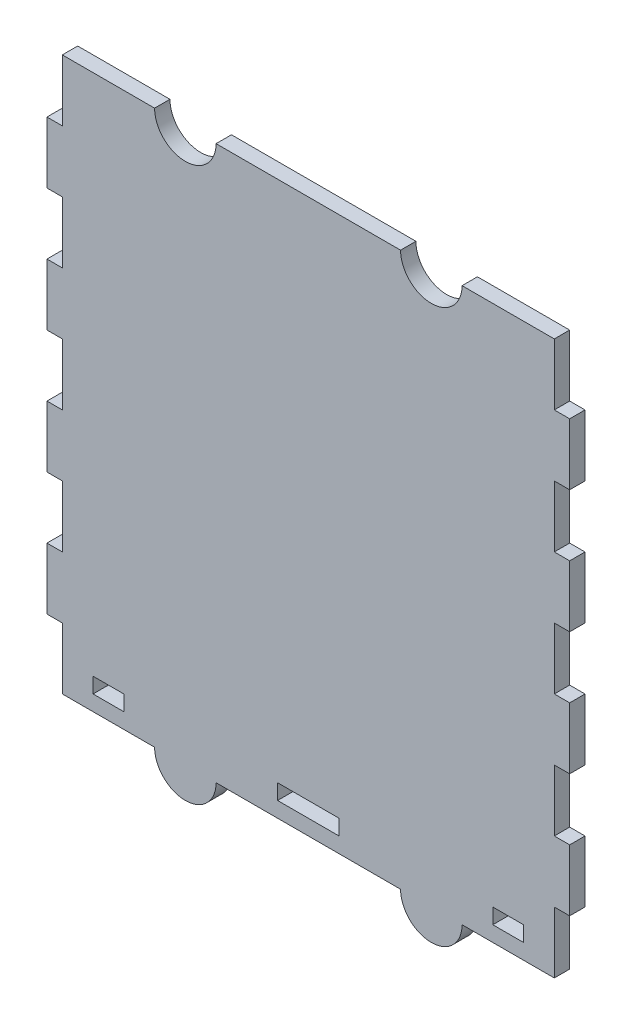
SolidWorks part; units mm, degrees
ref_plane "Front Plane" through (0, 0, 0) normal (0, 0, 1) x (1, 0, 0)
ref_plane "Top Plane" through (0, 0, 0) normal (0, 1, 0) x (1, 0, 0)
ref_plane "Right Plane" through (0, 0, 0) normal (1, 0, 0) x (0, 0, -1)
sketch "Sketch1" plane through (0, 0, 0) normal (0, 0, 1) x (1, 0, 0)
  line L0 (42.5, 60) -> (42.5, 50)
  line L1 (-15, 0) -> (15, 0)
  line L2 (25, 90) -> (40, 90)
  line L3 (-15, 90) -> (15, 90)
  line L4 (40, 0) -> (40, 10)
  line L5 (40, 80) -> (42.5, 80)
  line L6 (40, 80) -> (40, 90)
  line L7 (40, 70) -> (42.5, 70)
  line L8 (42.5, 80) -> (42.5, 70)
  line L9 (40, 50) -> (42.5, 50)
  line L10 (40, 60) -> (42.5, 60)
  line L11 (42.5, 40) -> (42.5, 30)
  line L12 (40, 30) -> (42.5, 30)
  line L13 (40, 40) -> (42.5, 40)
  line L14 (42.5, 20) -> (42.5, 10)
  line L15 (40, 10) -> (42.5, 10)
  line L16 (40, 20) -> (42.5, 20)
  line L17 (40, 20) -> (40, 30)
  line L18 (40, 40) -> (40, 50)
  line L19 (40, 60) -> (40, 70)
  line L20 (0, 90) -> (0, 0) construction
  line L21 (25, 0) -> (40, 0)
  line L22 (-5, 5) -> (-5, 2.5)
  line L23 (35, 5) -> (30, 5)
  line L24 (35, 5) -> (35, 2.5)
  line L25 (35, 2.5) -> (30, 2.5)
  line L26 (30, 5) -> (30, 2.5)
  line L27 (5, 5) -> (-5, 5)
  line L28 (5, 5) -> (5, 2.5)
  line L29 (5, 2.5) -> (-5, 2.5)
  line L30 (-30, 5) -> (-30, 2.5)
  line L31 (-35, 2.5) -> (-30, 2.5)
  line L32 (-35, 5) -> (-35, 2.5)
  line L33 (-35, 5) -> (-30, 5)
  line L34 (-25, 0) -> (-40, 0)
  line L35 (-40, 60) -> (-40, 70)
  line L36 (-40, 40) -> (-40, 50)
  line L37 (-40, 20) -> (-40, 30)
  line L38 (-40, 20) -> (-42.5, 20)
  line L39 (-40, 10) -> (-42.5, 10)
  line L40 (-42.5, 20) -> (-42.5, 10)
  line L41 (-40, 40) -> (-42.5, 40)
  line L42 (-40, 30) -> (-42.5, 30)
  line L43 (-42.5, 40) -> (-42.5, 30)
  line L44 (-40, 60) -> (-42.5, 60)
  line L45 (-40, 50) -> (-42.5, 50)
  line L46 (-42.5, 80) -> (-42.5, 70)
  line L47 (-40, 70) -> (-42.5, 70)
  line L48 (-40, 80) -> (-40, 90)
  line L49 (-40, 80) -> (-42.5, 80)
  line L50 (-40, 0) -> (-40, 10)
  line L51 (-25, 90) -> (-40, 90)
  line L52 (-42.5, 60) -> (-42.5, 50)
  arc A0 (15, 90) -> (25, 90) centre (20, 90) ccw
  arc A1 (15, 0) -> (25, 0) centre (20, 0) ccw
  arc A2 (-15, 0) -> (-25, 0) centre (-20, 0) cw
  arc A3 (-15, 90) -> (-25, 90) centre (-20, 90) cw
  point P36 (0, 0)
  point P44 (0, 2.5)
  point P45 (0, 5)
  dimension "D8" = 10
  dimension "D2" = 90
  dimension "D3" = 2.5
  dimension "D4" = 10
  dimension "D5" = 10
  dimension "D7" = 10
  dimension "D1" = 80
  dimension "D9" = 20
  dimension "D10" = 2.5
  dimension "D11" = 2.5
  dimension "D12" = 5
  dimension "D13" = 5
  dimension "D14" = 2.5
  dimension "D15" = 5
  dimension "D6" = 4
extrude "Boss-Extrude1" add sketch "Sketch1" along normal blind 2.5
equation "\"height\"=90"
equation "\"D2@Sketch1\"=\"height\""
equation "\"width\"=80"
equation "\"t\"=2.5"
equation "\"D3@Sketch1\"=\"t\""
equation "\"D1@Sketch1\"=\"width\""
equation "\"D9@Sketch1\"=\"width\"/4"
equation "\"D10@Sketch1\"=\"t\""
equation "\"D11@Sketch1\"=\"t\""
equation "\"D14@Sketch1\"=\"t\""
equation "\"D1@Boss-Extrude1\"=\"t\""
